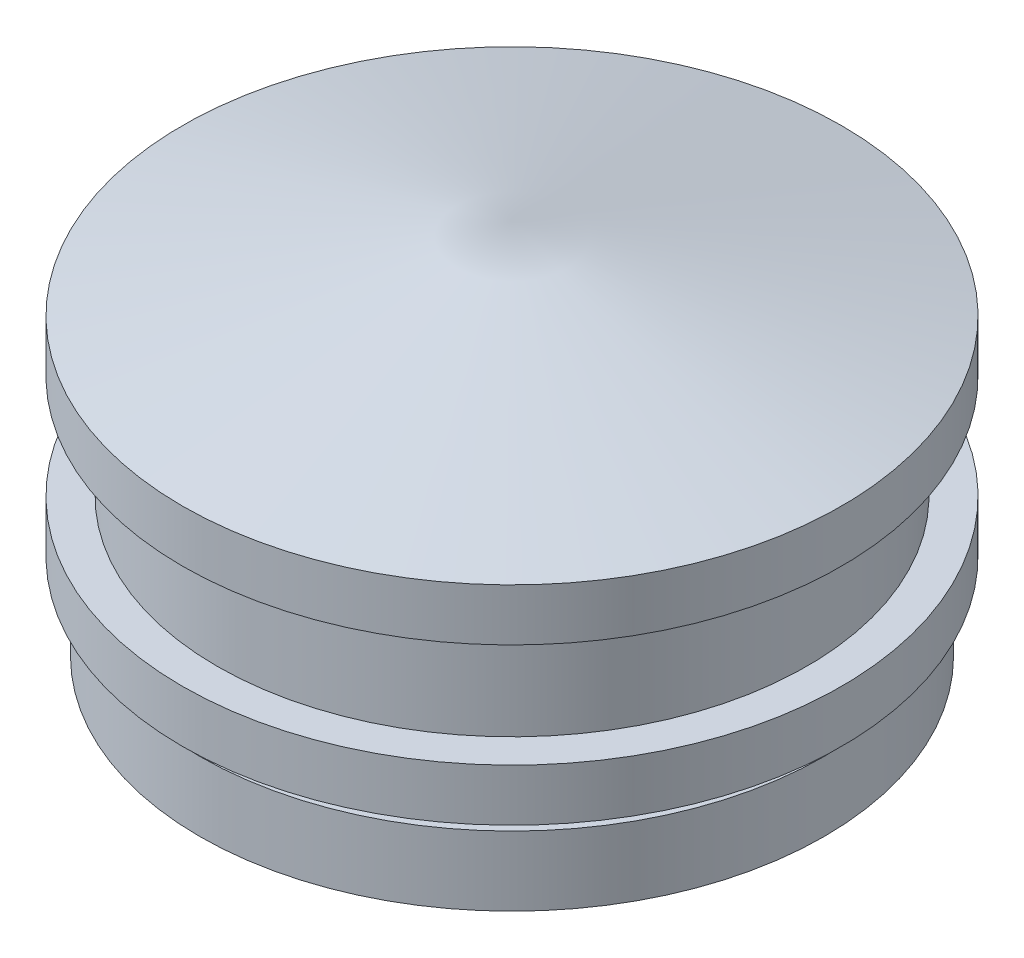
SolidWorks part; units mm, degrees
material "Резина"
ref_plane "Спереди" through (0, 0, 0) normal (0, 0, 1) x (1, 0, 0)
ref_plane "Сверху" through (0, 0, 0) normal (0, 1, 0) x (1, 0, 0)
ref_plane "Справа" through (0, 0, 0) normal (1, 0, 0) x (0, 0, -1)
sketch "Эскиз1" plane through (0, 0, 0) normal (0, 0, 1) x (1, 0, 0)
  line L0 (0, 0) -> (0, -46.3079) construction
  line L1 (0, 0) -> (9.5, -2.3686)
  line L2 (9.5, -2.3686) -> (9.5, -3.8686)
  line L3 (9.5, -3.8686) -> (8.5, -3.8686)
  line L4 (8.5, -3.8686) -> (8.5, -6.8686)
  line L5 (8.5, -6.8686) -> (9.5, -6.8686)
  line L6 (9.5, -6.8686) -> (9.5, -8.3686)
  line L7 (9.5, -8.3686) -> (8.5, -8.3686)
  line L8 (8.5, -8.3686) -> (8.5, -8.8686)
  line L9 (8.5, -8.8686) -> (9, -8.8686)
  line L10 (9, -8.8686) -> (9, -10.8686)
  line L11 (9, -10.8686) -> (0, -10.8686)
  line L12 (0, 0) -> (0, -10.8686)
  dimension "D1" = 1.5
  dimension "D2" = 1.5
  dimension "D3" = 1
  dimension "D4" = 0.5
  dimension "D5" = 104
  dimension "D6" = 2
  dimension "D7" = 8.5
  dimension "D8" = 3
  dimension "D9" = 19
revolve "Повернуть1" add sketch "Эскиз1" angle 360 about L0
